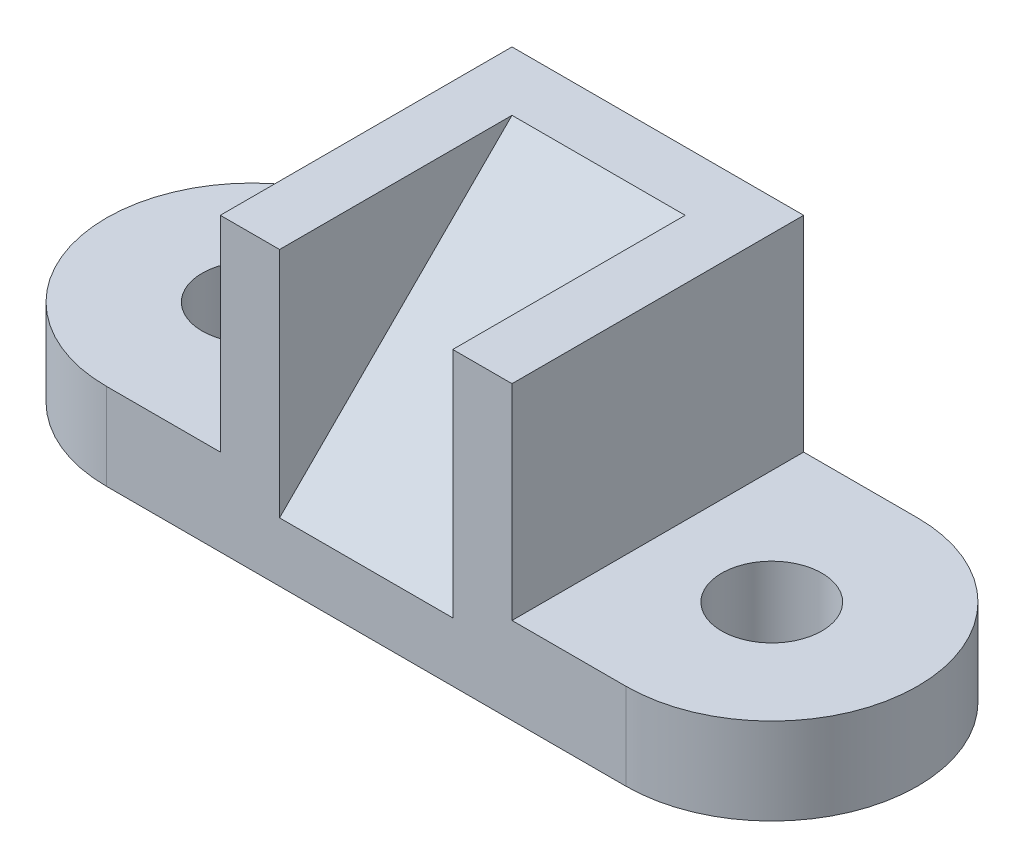
SolidWorks part; units mm, degrees
ref_plane "Front Plane" through (0, 0, 0) normal (0, 0, 1) x (1, 0, 0)
ref_plane "Top Plane" through (0, 0, 0) normal (0, 1, 0) x (1, 0, 0)
ref_plane "Right Plane" through (0, 0, 0) normal (1, 0, 0) x (0, 0, -1)
sketch "Sketch1" plane through (0, 0, 0) normal (0, 1, 0) x (1, 0, 0)
  line L0 (-57, 0) -> (57, 0) construction
  line L1 (-57, 32) -> (57, 32)
  line L2 (-57, -32) -> (57, -32)
  arc A0 (-57, 32) -> (-57, -32) centre (-57, 0) ccw
  arc A1 (57, -32) -> (57, 32) centre (57, 0) ccw
  circle A2 centre (-57, 0) radius 11
  circle A3 centre (57, 0) radius 11
  point P2 (0, 0)
  dimension "D2" = 22
  dimension "D4" = 32
  dimension "D1" = 114
  dimension "D3" = 64
extrude "Boss-Extrude1" add sketch "Sketch1" along normal blind 19
sketch "Sketch2" plane through (0, 19, 0) normal (0, 1, 0) x (1, 0, 0)
  line L0 (-57, -32) -> (57, -32) construction
  line L1 (-32, 32) -> (32, 32)
  line L2 (-32, 32) -> (-32, -32)
  line L3 (-32, -32) -> (32, -32)
  line L4 (32, 32) -> (32, -32)
  line L5 (-32, 32) -> (32, -32) construction
  line L6 (-32, -32) -> (32, 32) construction
  point P0 (0, 0)
  dimension "D1" = 64
extrude "Boss-Extrude2" add sketch "Sketch2" along normal blind 45
sketch "Sketch7" plane through (0, 0, 32) normal (0, 0, 1) x (1, 0, 0)
  line L0 (-32, 64) -> (32, 64) construction
  line L1 (-19, 64) -> (19, 64)
  line L2 (-19, 64) -> (-19, 13)
  line L3 (-19, 13) -> (19, 13)
  line L4 (19, 64) -> (19, 13)
  line L6 (-57, 0) -> (57, 0) construction
  line L7 (32, 64) -> (32, 19) construction
  dimension "D1" = 13
  dimension "D2" = 13
  dimension "D3" = 38
extrude "Cut-Extrude3" cut sketch "Sketch7" against normal blind 51 and the other way through all
sketch "Sketch11" plane through (-19, 0, 0) normal (1, 0, 0) x (0, 0, -1)
  line L0 (-32, 13) -> (19, 64)
  line L1 (-32, 64) -> (32, 64) construction
  line L2 (19, 64) -> (19, 13)
  line L3 (19, 13) -> (-32, 13)
  point P4 (0, 0)
  point P6 (-32, 13)
  dimension "D1" = 51
extrude "Boss-Extrude3" add sketch "Sketch11" along normal blind 51
